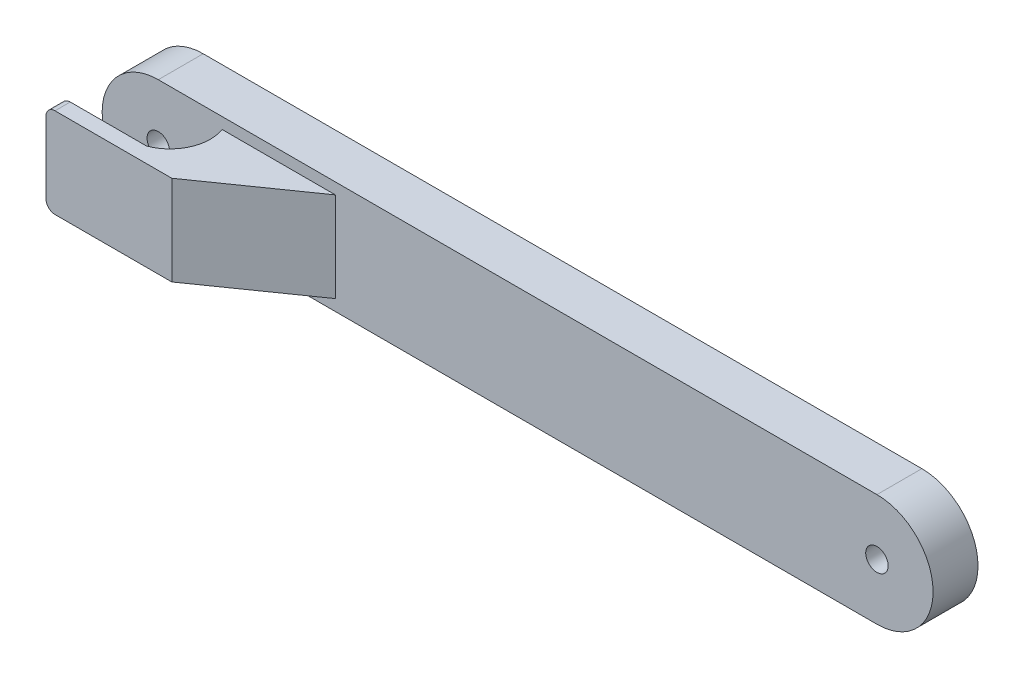
SolidWorks part; units mm, degrees
ref_plane "Front" through (0, 0, 0) normal (0, 0, 1) x (1, 0, 0)
ref_plane "Top" through (0, 0, 0) normal (0, 1, 0) x (1, 0, 0)
ref_plane "Right" through (0, 0, 0) normal (1, 0, 0) x (0, 0, -1)
sketch "Sketch1" plane through (0, 0, 0) normal (0, 0, 1) x (1, 0, 0)
  line L0 (299.8703, -79.0606) -> (503.0703, -79.0606) construction
  line L1 (299.8703, -63.1856) -> (503.0703, -63.1856)
  line L2 (299.8703, -94.9356) -> (503.0703, -94.9356)
  line L3 (401.4703, -94.9356) -> (401.4703, -63.1856) construction
  arc A0 (299.8703, -63.1856) -> (299.8703, -94.9356) centre (299.8703, -79.0606) ccw
  arc A1 (503.0703, -94.9356) -> (503.0703, -63.1856) centre (503.0703, -79.0606) ccw
  circle A2 centre (299.8703, -79.0606) radius 3.175
  circle A3 centre (503.0703, -79.0606) radius 3.175
  point P2 (401.4703, -79.0606)
  dimension "D1" = 203.2
  dimension "D2" = 15.875
  dimension "D3" = 31.75
extrude "Boss-Extrude1" add sketch "Sketch1" along normal blind 12.7
sketch "Sketch2" plane through (0, 0, 0) normal (0, 0, -1) x (-1, 0, 0)
  line L5 (-477.6703, -66.3606) -> (-477.6703, -91.7606)
  line L6 (-513.2303, -91.7606) -> (-477.6703, -91.7606)
  line L7 (-515.7703, -89.2206) -> (-515.7703, -68.9006)
  line L8 (-513.2303, -66.3606) -> (-477.6703, -66.3606)
  line L10 (-515.7703, -91.7606) -> (-490.3703, -66.3606) construction
  line L11 (-515.7703, -66.3606) -> (-490.3703, -91.7606) construction
  arc A0 (-513.2303, -91.7606) -> (-515.7703, -89.2206) centre (-513.2303, -89.2206) cw
  arc A3 (-515.7703, -68.9006) -> (-513.2303, -66.3606) centre (-513.2303, -68.9006) cw
  point P0 (-503.0703, -79.0606)
  dimension "D3" = 2.54
  dimension "D1" = 25.4
  dimension "D2" = 25.4
  dimension "D4" = 35.56
ref_plane "Plane5" through (401.447, 0, 0) normal (1, 0, 0) x (0, 0, -1)
surface "Surface-MidSurface2" parameters "D0"=50000
sketch "Sketch7" plane through (0, 0, 12.7) normal (0, 0, 1) x (1, 0, 0)
  line L0 (310.0303, -66.3606) -> (312.5703, -66.3606)
  line L1 (289.7103, -91.7606) -> (310.0303, -91.7606)
  line L2 (287.1703, -89.2206) -> (287.1703, -68.9006)
  line L3 (289.7103, -66.3606) -> (310.0303, -66.3606)
  line L5 (287.1703, -91.7606) -> (312.5703, -66.3606) construction
  line L6 (287.1703, -66.3606) -> (312.5703, -91.7606) construction
  line L7 (312.5703, -66.3606) -> (322.7303, -66.3606)
  line L8 (322.7303, -66.3606) -> (322.7303, -91.7606)
  line L9 (310.0303, -91.7606) -> (322.7303, -91.7606)
  arc A0 (289.7103, -91.7606) -> (287.1703, -89.2206) centre (289.7103, -89.2206) cw
  arc A3 (287.1703, -68.9006) -> (289.7103, -66.3606) centre (289.7103, -68.9006) cw
  point P0 (299.8703, -79.0606)
  dimension "D3" = 2.54
  dimension "D1" = 25.4
  dimension "D2" = 25.4
  dimension "D4" = 10.16
extrude "Boss-Extrude8" add sketch "Sketch7" along normal blind 19.05
sketch "Sketch8" plane through (0, -66.3606, 0) normal (0, 1, 0) x (1, 0, 0)
  line L0 (287.1703, -12.7) -> (317.9043, -12.7)
  line L1 (503.0703, -12.7) -> (299.8703, -12.7) construction
  line L2 (287.1703, -12.7) -> (287.1703, -27.432)
  line L3 (287.1703, -31.75) -> (287.1703, -12.7) construction
  line L4 (287.1703, -27.432) -> (311.3003, -27.432)
  arc A0 (317.9043, -12.7) -> (311.3003, -27.432) centre (307.218, -16.7558) cw
  dimension "D1" = 30.734
  dimension "D2" = 14.732
  dimension "D3" = 24.13
extrude "Cut-Extrude3" cut sketch "Sketch8" against normal blind 41.148
sketch "Sketch9" plane through (0, -66.3606, 0) normal (0, 1, 0) x (1, 0, 0)
  line L0 (322.7303, -31.75) -> (349.9365, -12.7)
  line L1 (503.0703, -12.7) -> (299.8703, -12.7) construction
  line L4 (322.7303, -12.7) -> (349.9365, -12.7)
  line L5 (322.7303, -31.75) -> (322.7303, -12.7)
  dimension "D1" = 35
extrude "Boss-Extrude9" add sketch "Sketch9" against normal blind 25.4
